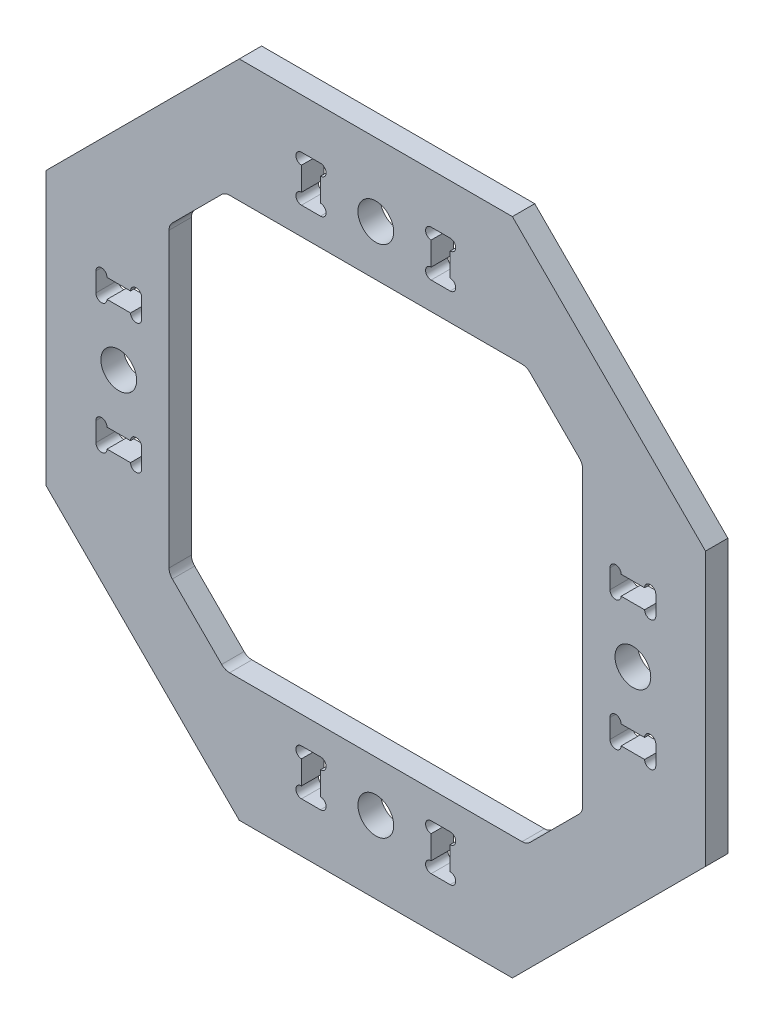
SolidWorks part; units mm, degrees
material "Thornel VCB-20 Carbon Cloth"
ref_plane "Front Plane" through (0, 0, 0) normal (0, 0, 1) x (1, 0, 0)
ref_plane "Top Plane" through (0, 0, 0) normal (0, 1, 0) x (1, 0, 0)
ref_plane "Right Plane" through (0, 0, 0) normal (1, 0, 0) x (0, 0, -1)
sketch "Sketch1" plane through (0, 0, 0) normal (0, 0, 1) x (1, 0, 0)
  line L5 (29.5, 12.2193) -> (12.2193, 29.5)
  line L6 (12.2193, 29.5) -> (-12.2193, 29.5)
  line L7 (-12.2193, 29.5) -> (-29.5, 12.2193)
  line L8 (-29.5, 12.2193) -> (-29.5, -12.2193)
  line L9 (-29.5, -12.2193) -> (-12.2193, -29.5)
  line L10 (-12.2193, -29.5) -> (12.2193, -29.5)
  line L11 (12.2193, -29.5) -> (29.5, -12.2193)
  line L16 (-20.95, -4.95) -> (-25.05, -4.95)
  line L17 (-20.95, -6.65) -> (-20.95, -4.95)
  line L18 (-25.05, -6.65) -> (-20.95, -6.65)
  line L19 (-25.05, -4.95) -> (-25.05, -6.65)
  line L20 (-20.95, -4.95) -> (-25.05, -4.95)
  line L21 (-20.95, -6.65) -> (-20.95, -4.95)
  line L22 (-25.05, -6.65) -> (-20.95, -6.65)
  line L23 (-25.05, -4.95) -> (-25.05, -6.65)
  line L24 (-4.95, 20.95) -> (-4.95, 25.05)
  line L25 (-6.65, 20.95) -> (-4.95, 20.95)
  line L26 (-6.65, 25.05) -> (-6.65, 20.95)
  line L27 (-4.95, 25.05) -> (-6.65, 25.05)
  line L28 (-20.95, 6.65) -> (-25.05, 6.65)
  line L29 (-20.95, 4.95) -> (-20.95, 6.65)
  line L30 (-25.05, 4.95) -> (-20.95, 4.95)
  line L31 (-25.05, 6.65) -> (-25.05, 4.95)
  line L32 (-20.95, 6.65) -> (-25.05, 6.65)
  line L33 (-20.95, 4.95) -> (-20.95, 6.65)
  line L34 (-25.05, 4.95) -> (-20.95, 4.95)
  line L35 (-25.05, 6.65) -> (-25.05, 4.95)
  line L36 (6.65, 20.95) -> (6.65, 25.05)
  line L37 (4.95, 20.95) -> (6.65, 20.95)
  line L38 (4.95, 25.05) -> (4.95, 20.95)
  line L39 (6.65, 25.05) -> (4.95, 25.05)
  line L40 (20.95, 4.95) -> (25.05, 4.95)
  line L41 (20.95, 6.65) -> (20.95, 4.95)
  line L42 (25.05, 6.65) -> (20.95, 6.65)
  line L43 (25.05, 4.95) -> (25.05, 6.65)
  line L44 (20.95, -6.65) -> (25.05, -6.65)
  line L45 (20.95, -4.95) -> (20.95, -6.65)
  line L46 (25.05, -4.95) -> (20.95, -4.95)
  line L47 (25.05, -6.65) -> (25.05, -4.95)
  line L48 (4.95, -20.95) -> (4.95, -25.05)
  line L49 (6.65, -20.95) -> (4.95, -20.95)
  line L50 (6.65, -25.05) -> (6.65, -20.95)
  line L51 (4.95, -25.05) -> (6.65, -25.05)
  line L52 (-6.65, -20.95) -> (-6.65, -25.05)
  line L53 (-4.95, -20.95) -> (-6.65, -20.95)
  line L54 (-4.95, -25.05) -> (-4.95, -20.95)
  line L55 (-6.65, -25.05) -> (-4.95, -25.05)
  line L116 (29.5, -12.2193) -> (29.5, 12.2193)
  circle A8 centre (0, 0) radius 29.5 construction
  circle A16 centre (-23, 0) radius 1.6 construction
  circle A17 centre (-23, 0) radius 1.6
  circle A18 centre (0, 23) radius 1.6
  circle A19 centre (23, 0) radius 1.6
  circle A20 centre (0, -23) radius 1.6
  point P38 (0, 0)
  dimension "D1" = 59
  dimension "D2" = 0.05
  dimension "D3" = 0.05
  dimension "D4" = 4
extrude "Boss-Extrude1" add sketch "Sketch1" against normal blind 2
sketch "Sketch2" plane through (0, 0, 0) normal (0, 0, -1) x (-1, 0, 0)
  line L0 (18.5, 18.5) -> (-18.5, -18.5) construction
  line L1 (18.5, -18.5) -> (-18.5, -18.5)
  line L2 (18.5, -18.5) -> (18.5, 18.5)
  line L3 (18.5, 18.5) -> (-18.5, 18.5)
  line L4 (-18.5, -18.5) -> (-18.5, 18.5)
  line L5 (18.5, 13.5) -> (13.5, 18.5)
  line L6 (13.5, -18.5) -> (18.5, -13.5)
  line L7 (-18.5, -13.5) -> (-13.5, -18.5)
  line L8 (-13.5, 18.5) -> (-18.5, 13.5)
  line L9 (12.2193, 29.5) -> (29.5, 12.2193) construction
  point P15 (0, 0)
  dimension "D1" = 37
  dimension "D2" = 4
  dimension "D3" = 6.8726
  dimension "D4" = 7.0711
  dimension "D5" = 27
extrude "Cut-Extrude1" cut sketch "Sketch2" along normal up to next contours L0 L5 L2 L6 L1 L7 | L5 L0 L7 L4 L8 L3
fillet "Fillet2" radius 1 8 edges at (-18.5, -13.5, -1) (-13.5, -18.5, -1) (13.5, -18.5, -1) (18.5, -13.5, -1) (18.5, 13.5, -1) (13.5, 18.5, -1) (-13.5, 18.5, -1) (-18.5, 13.5, -1)
sketch "Sketch4" plane through (0, 0, 0) normal (0, 0, 1) x (1, 0, 0)
  line L0 (-20.95, 6.65) -> (-25.05, 6.65) construction
  line L1 (-25.05, 4.95) -> (-20.95, 4.95) construction
  line L2 (-20.95, -4.95) -> (-25.05, -4.95) construction
  line L3 (-25.05, -6.65) -> (-20.95, -6.65) construction
  circle A0 centre (-24.55, 6.65) radius 0.5
  circle A1 centre (-21.45, 6.65) radius 0.5
  circle A2 centre (-21.45, 4.95) radius 0.5
  circle A3 centre (-24.55, 4.95) radius 0.5
  circle A4 centre (-24.55, -4.95) radius 0.5
  circle A5 centre (-24.55, -6.65) radius 0.5
  circle A6 centre (-21.45, -4.95) radius 0.5
  circle A7 centre (-21.45, -6.65) radius 0.5
  circle A8 centre (6.65, 21.45) radius 0.5
  circle A9 centre (4.95, 21.45) radius 0.5
  circle A10 centre (4.95, 24.55) radius 0.5
  circle A11 centre (-4.95, 24.55) radius 0.5
  circle A12 centre (-6.65, 24.55) radius 0.5
  circle A13 centre (-4.95, 21.45) radius 0.5
  circle A14 centre (-6.65, 21.45) radius 0.5
  circle A15 centre (21.45, -6.65) radius 0.5
  circle A16 centre (21.45, -4.95) radius 0.5
  circle A17 centre (24.55, -4.95) radius 0.5
  circle A18 centre (24.55, 4.95) radius 0.5
  circle A19 centre (24.55, 6.65) radius 0.5
  circle A20 centre (21.45, 4.95) radius 0.5
  circle A21 centre (21.45, 6.65) radius 0.5
  circle A22 centre (-6.65, -21.45) radius 0.5
  circle A23 centre (-4.95, -21.45) radius 0.5
  circle A24 centre (-4.95, -24.55) radius 0.5
  circle A25 centre (4.95, -24.55) radius 0.5
  circle A26 centre (6.65, -24.55) radius 0.5
  circle A27 centre (4.95, -21.45) radius 0.5
  circle A28 centre (6.65, -21.45) radius 0.5
  circle A29 centre (6.65, 24.55) radius 0.5
  circle A30 centre (24.55, -6.65) radius 0.5
  circle A31 centre (-6.65, -24.55) radius 0.5
  point P77 (0, 0)
  dimension "D1" = 1
  dimension "D2" = 4
extrude "Cut-Extrude3" cut sketch "Sketch4" against normal up to next (2 mm away)
